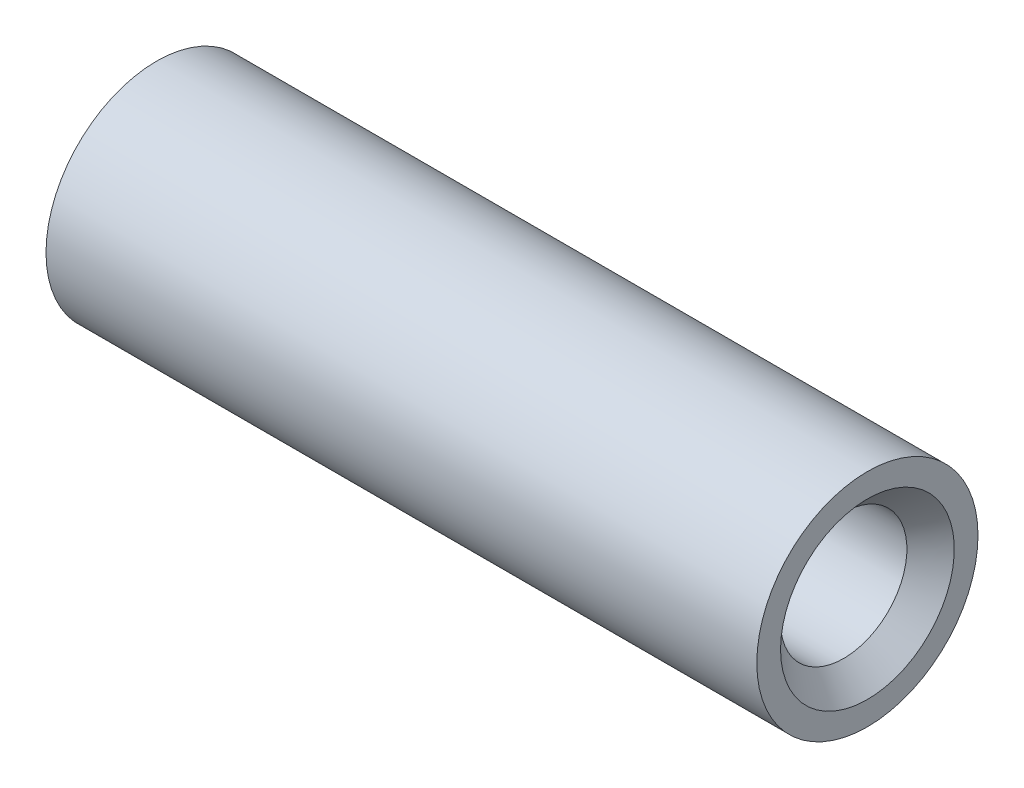
SolidWorks part; units mm, degrees
ref_plane "Front" through (0, 0, 0) normal (0, 0, 1) x (1, 0, 0)
ref_plane "Top" through (0, 0, 0) normal (0, 1, 0) x (1, 0, 0)
ref_plane "Right" through (0, 0, 0) normal (1, 0, 0) x (0, 0, -1)
sketch "Sketch1" plane through (0, 0, 0) normal (0, 0, 1) x (1, 0, 0)
  line L0 (0, 0) -> (25.4984, 0) construction
  line L1 (-2.5, 0) -> (-2.5, 4)
  line L2 (-2.5, 4) -> (-22.5, 4)
  line L3 (-22.5, 4) -> (-22.5, 7.0014)
  line L4 (-22.5, 7.0014) -> (22.5, 7.0014)
  line L5 (22.5, 7.0014) -> (22.5, 4)
  line L6 (22.5, 4) -> (2.5, 4)
  line L7 (2.5, 4) -> (2.5, 0)
  line L8 (2.5, 0) -> (-2.5, 0)
  line L9 (0, 0) -> (0, 11.8157) construction
  dimension "D1" = 8
  dimension "D2" = 8
  dimension "D3" = 20
  dimension "D4" = 5
  dimension "D5" = 3.0014
revolve "Revolve1" add sketch "Sketch1" angle 360 about L0
chamfer "Chamfer1" distance 1.5 angle 45 2 edges at (-22.5, 0, 4) (22.5, 0, 4)
